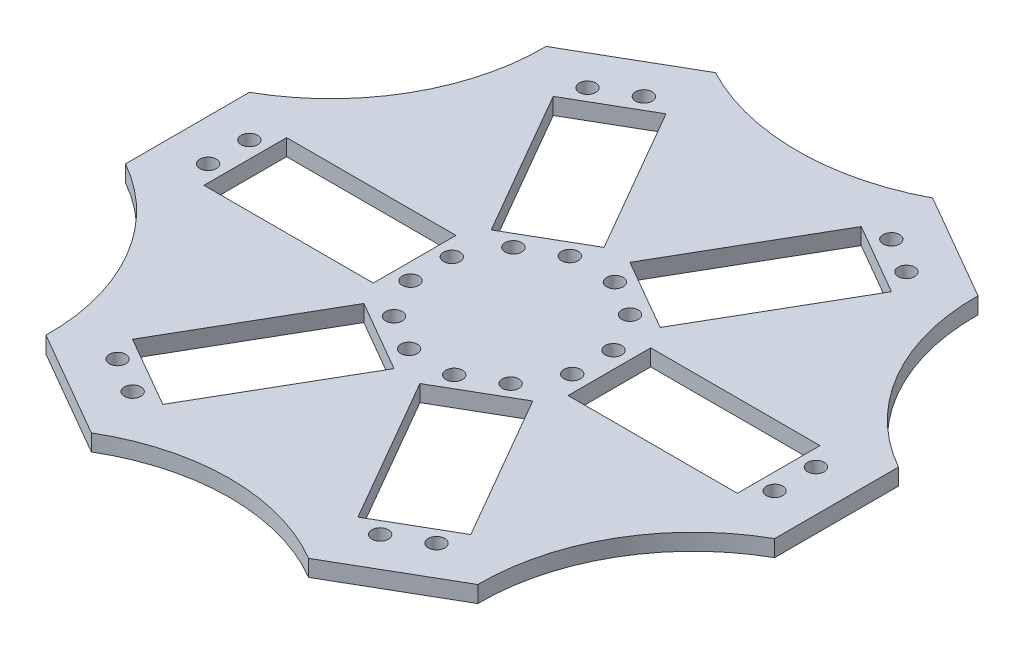
SolidWorks part; units mm, degrees
other "标注1"
sketch "草图5" plane through (-78.5812, 4, 75.5533) normal (-0.7481, 0.619, 0.2389) x (0.4912, 0.2747, 0.8266)
ref_plane "前视基准面" through (0, 0, 0) normal (0, 0, 1) x (1, 0, 0)
ref_plane "上视基准面" through (0, 0, 0) normal (0, 1, 0) x (1, 0, 0)
ref_plane "右视基准面" through (0, 0, 0) normal (1, 0, 0) x (0, 0, -1)
other "Configuration Table"
sketch "草图1" plane through (0, 0, 0) normal (0, 1, 0) x (1, 0, 0)
  line L0 (0, 0) -> (80, 0) construction
  line L1 (80, 0) -> (40, 69.282) construction
  line L2 (40, 69.282) -> (-40, 69.282) construction
  line L3 (-40, 69.282) -> (-80, 0) construction
  line L4 (-80, 0) -> (-40, -69.282) construction
  line L5 (-40, -69.282) -> (40, -69.282) construction
  line L6 (40, -69.282) -> (80, 0) construction
  line L7 (78.5812, 15) -> (78.5812, -15)
  line L8 (40, 69.282) -> (-40, -69.282) construction
  line L10 (0, 0) -> (-80, 0) construction
  line L11 (26.3002, 75.5533) -> (52.281, 60.5533)
  line L12 (-52.281, 60.5533) -> (-26.3002, 75.5533)
  line L13 (-78.5812, 15) -> (-78.5812, -15)
  line L14 (-52.281, -60.5533) -> (-26.3002, -75.5533)
  line L15 (26.3002, -75.5533) -> (52.281, -60.5533)
  line L16 (0, 0) -> (103.923, 60) construction
  line L17 (0, 0) -> (-103.923, -60) construction
  line L18 (0, 0) -> (0, -120) construction
  line L19 (0, 0) -> (0, 9.9658) construction
  line L20 (0, 125.523) -> (0, 0) construction
  line L21 (0, 0) -> (-103.923, 60) construction
  line L22 (0, 0) -> (103.923, -60) construction
  circle A0 centre (0, 0) radius 80 construction
  arc A2 (52.281, 60.5533) -> (78.5812, 15) centre (103.923, 60) ccw
  arc A3 (52.281, -60.5533) -> (78.5812, -15) centre (103.923, -60) cw
  arc A4 (26.3002, -75.5533) -> (-26.3002, -75.5533) centre (0, -120) ccw
  arc A5 (-52.281, -60.5533) -> (-78.5812, -15) centre (-103.923, -60) ccw
  arc A6 (-52.281, 60.5533) -> (-78.5812, 15) centre (-103.923, 60) cw
  arc A7 (-26.3002, 75.5533) -> (26.3002, 75.5533) centre (0, 125.523) ccw
extrude "凸台-拉伸1" add sketch "草图1" along normal blind 4
sketch "草图3" plane through (0, 0, 0) normal (0, 1, 0) x (1, 0, 0)
  line L0 (0, 0) -> (68.5812, 0) construction
  line L1 (68.5812, 0) -> (68.5812, 5) construction
  line L2 (68.5812, 0) -> (68.5812, -5) construction
  line L3 (78.5812, -15) -> (78.5812, 15) construction
  line L4 (68.5812, 5) -> (19.5812, 5) construction
  line L5 (19.5812, -5) -> (23.5812, -5) construction
  line L6 (23.5812, -5) -> (64.5812, -5) construction
  line L7 (68.5812, -5) -> (64.5812, -5) construction
  line L9 (23.5812, 10) -> (64.5812, 10)
  line L10 (23.5812, 10) -> (23.5812, -10)
  line L11 (23.5812, -10) -> (64.5812, -10)
  line L12 (64.5812, 10) -> (64.5812, -10)
  circle A0 centre (68.5812, 5) radius 2
  circle A1 centre (68.5812, -5) radius 2
  circle A2 centre (19.5812, 5) radius 2
  circle A3 centre (19.5812, -5) radius 2
  point P17 (23.5812, 0)
  dimension "D4" = 4
  dimension "D5" = 4
  dimension "D1" = 5
  dimension "D2" = 5
  dimension "D3" = 10
  dimension "D6" = 49
  dimension "D7" = 41
  dimension "D8" = 20
  dimension "D9" = 41
extrude "切除-拉伸3" cut sketch "草图3" against normal mid plane 50
sketch "草图4" plane through (0, 0, 0) normal (0, 0, 1) x (1, 0, 0)
  line L0 (0, 0) -> (0, 56.081) construction
pattern_circular "阵列(圆周)1" count 6 over 360 about axis through (0, 0, 0) along (0, 1, 0) of "切除-拉伸3"
sketch "草图2" plane through (0, 0, 0) normal (0, 1, 0) x (1, 0, 0)
  line L0 (0, 0) -> (68.5812, 0) construction
  line L1 (68.5812, 0) -> (68.5812, 5) construction
  line L2 (68.5812, 0) -> (68.5812, -5) construction
  line L3 (78.5812, -15) -> (78.5812, 15) construction
  circle A0 centre (68.5812, 5) radius 2
  circle A1 centre (68.5812, -5) radius 2
  dimension "D4" = 4
  dimension "D5" = 4
  dimension "D1" = 5
  dimension "D2" = 5
  dimension "D3" = 10
